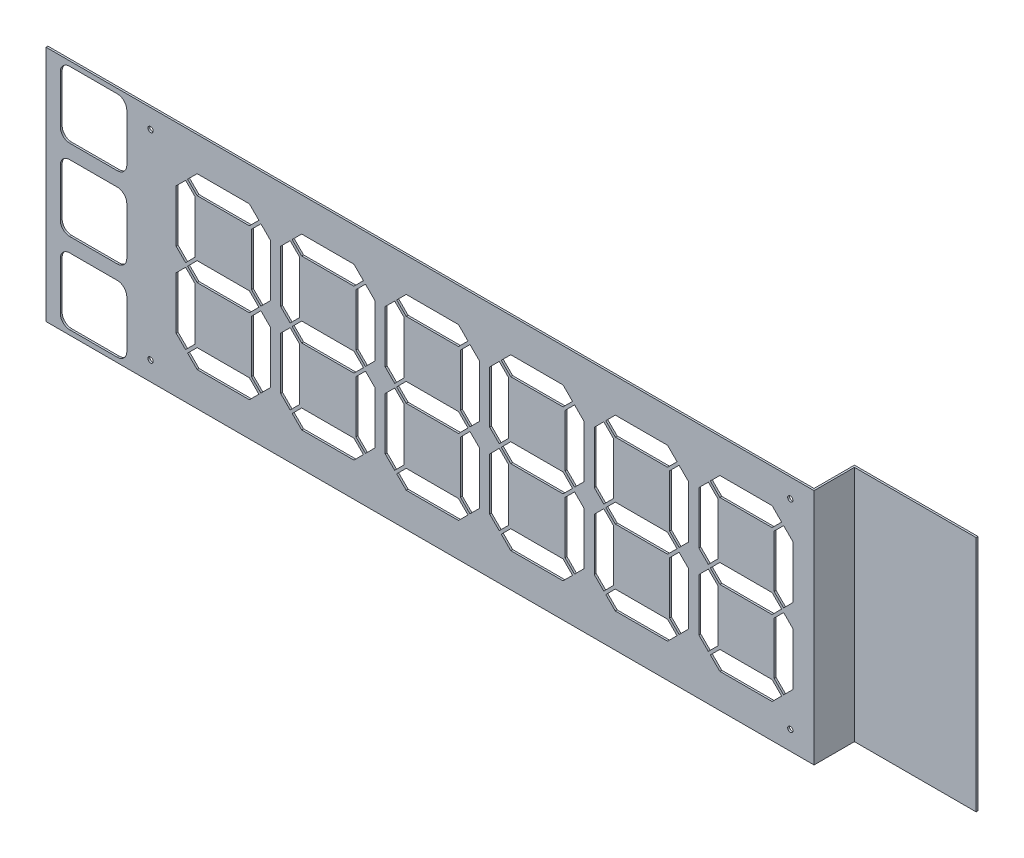
SolidWorks part; units mm, degrees
ref_plane "Plan de face" through (0, 0, 0) normal (0, 0, 1) x (1, 0, 0)
ref_plane "Plan de dessus" through (0, 0, 0) normal (0, 1, 0) x (1, 0, 0)
ref_plane "Plan de droite" through (0, 0, 0) normal (1, 0, 0) x (0, 0, -1)
sketch "Esquisse10" plane through (0, 0, 0) normal (0, 0, 1) x (1, 0, 0)
  line L264 (107.7211, -70.7055) -> (97.7211, -60.7055)
  line L265 (97.7211, -60.7055) -> (42.7211, -60.7055)
  line L266 (42.7211, -60.7055) -> (32.7211, -70.7055)
  line L267 (32.7211, -70.7055) -> (42.7211, -80.7055)
  line L268 (42.7211, -80.7055) -> (97.7211, -80.7055)
  line L269 (97.7211, -80.7055) -> (107.7211, -70.7055)
  line L270 (109.8425, -68.5842) -> (119.8425, -58.5842)
  line L271 (119.8425, -58.5842) -> (119.8425, -3.5842)
  line L272 (119.8425, -3.5842) -> (109.8425, 6.4158)
  line L273 (109.8425, 6.4158) -> (99.8425, -3.5842)
  line L274 (99.8425, -3.5842) -> (99.8425, -58.5842)
  line L275 (99.8425, -58.5842) -> (109.8425, -68.5842)
  line L276 (30.5998, -68.5842) -> (40.5998, -58.5842)
  line L277 (40.5998, -58.5842) -> (40.5998, -3.5842)
  line L278 (40.5998, -3.5842) -> (30.5998, 6.4158)
  line L279 (30.5998, 6.4158) -> (20.5998, -3.5842)
  line L280 (20.5998, -3.5842) -> (20.5998, -58.5842)
  line L281 (20.5998, -58.5842) -> (30.5998, -68.5842)
  line L282 (107.7211, 8.5372) -> (97.7211, 18.5372)
  line L283 (97.7211, 18.5372) -> (42.7211, 18.5372)
  line L284 (42.7211, 18.5372) -> (32.7211, 8.5372)
  line L285 (32.7211, 8.5372) -> (42.7211, -1.4628)
  line L286 (42.7211, -1.4628) -> (97.7211, -1.4628)
  line L287 (97.7211, -1.4628) -> (107.7211, 8.5372)
  line L288 (109.8425, 10.6585) -> (119.8425, 20.6585)
  line L289 (119.8425, 20.6585) -> (119.8425, 75.6585)
  line L290 (119.8425, 75.6585) -> (109.8425, 85.6585)
  line L291 (109.8425, 85.6585) -> (99.8425, 75.6585)
  line L292 (99.8425, 75.6585) -> (99.8425, 20.6585)
  line L293 (99.8425, 20.6585) -> (109.8425, 10.6585)
  line L294 (107.7211, 87.7798) -> (97.7211, 97.7798)
  line L295 (97.7211, 97.7798) -> (42.7211, 97.7798)
  line L296 (42.7211, 97.7798) -> (32.7211, 87.7798)
  line L297 (32.7211, 87.7798) -> (42.7211, 77.7798)
  line L298 (42.7211, 77.7798) -> (97.7211, 77.7798)
  line L299 (97.7211, 77.7798) -> (107.7211, 87.7798)
  line L300 (30.5998, 10.6585) -> (40.5998, 20.6585)
  line L301 (40.5998, 20.6585) -> (40.5998, 75.6585)
  line L302 (40.5998, 75.6585) -> (30.5998, 85.6585)
  line L303 (30.5998, 85.6585) -> (20.5998, 75.6585)
  line L304 (20.5998, 75.6585) -> (20.5998, 20.6585)
  line L305 (20.5998, 20.6585) -> (30.5998, 10.6585)
  line L306 (-0.1575, 10.6585) -> (9.8425, 20.6585)
  line L307 (9.8425, 20.6585) -> (9.8425, 75.6585)
  line L308 (9.8425, 75.6585) -> (-0.1575, 85.6585)
  line L309 (-0.1575, 85.6585) -> (-10.1575, 75.6585)
  line L310 (-10.1575, 75.6585) -> (-10.1575, 20.6585)
  line L311 (-10.1575, 20.6585) -> (-0.1575, 10.6585)
  line L312 (-0.1575, -68.5842) -> (9.8425, -58.5842)
  line L313 (9.8425, -58.5842) -> (9.8425, -3.5842)
  line L314 (9.8425, -3.5842) -> (-0.1575, 6.4158)
  line L315 (-0.1575, 6.4158) -> (-10.1575, -3.5842)
  line L316 (-10.1575, -3.5842) -> (-10.1575, -58.5842)
  line L317 (-10.1575, -58.5842) -> (-0.1575, -68.5842)
  line L318 (-2.2789, -70.7055) -> (-12.2789, -60.7055)
  line L319 (-12.2789, -60.7055) -> (-67.2789, -60.7055)
  line L320 (-67.2789, -60.7055) -> (-77.2789, -70.7055)
  line L321 (-77.2789, -70.7055) -> (-67.2789, -80.7055)
  line L322 (-67.2789, -80.7055) -> (-12.2789, -80.7055)
  line L323 (-12.2789, -80.7055) -> (-2.2789, -70.7055)
  line L324 (-79.4002, -68.5842) -> (-69.4002, -58.5842)
  line L325 (-69.4002, -58.5842) -> (-69.4002, -3.5842)
  line L326 (-69.4002, -3.5842) -> (-79.4002, 6.4158)
  line L327 (-79.4002, 6.4158) -> (-89.4002, -3.5842)
  line L328 (-89.4002, -3.5842) -> (-89.4002, -58.5842)
  line L329 (-89.4002, -58.5842) -> (-79.4002, -68.5842)
  line L330 (-2.2789, 8.5372) -> (-12.2789, 18.5372)
  line L331 (-12.2789, 18.5372) -> (-67.2789, 18.5372)
  line L332 (-67.2789, 18.5372) -> (-77.2789, 8.5372)
  line L333 (-77.2789, 8.5372) -> (-67.2789, -1.4628)
  line L334 (-67.2789, -1.4628) -> (-12.2789, -1.4628)
  line L335 (-12.2789, -1.4628) -> (-2.2789, 8.5372)
  line L336 (-79.4002, 10.6585) -> (-69.4002, 20.6585)
  line L337 (-69.4002, 20.6585) -> (-69.4002, 75.6585)
  line L338 (-69.4002, 75.6585) -> (-79.4002, 85.6585)
  line L339 (-79.4002, 85.6585) -> (-89.4002, 75.6585)
  line L340 (-89.4002, 75.6585) -> (-89.4002, 20.6585)
  line L341 (-89.4002, 20.6585) -> (-79.4002, 10.6585)
  line L342 (-2.2789, 87.7798) -> (-12.2789, 97.7798)
  line L343 (-12.2789, 97.7798) -> (-67.2789, 97.7798)
  line L344 (-67.2789, 97.7798) -> (-77.2789, 87.7798)
  line L345 (-77.2789, 87.7798) -> (-67.2789, 77.7798)
  line L346 (-67.2789, 77.7798) -> (-12.2789, 77.7798)
  line L347 (-12.2789, 77.7798) -> (-2.2789, 87.7798)
  line L348 (-110.1575, -68.5842) -> (-100.1575, -58.5842)
  line L349 (-100.1575, -58.5842) -> (-100.1575, -3.5842)
  line L350 (-100.1575, -3.5842) -> (-110.1575, 6.4158)
  line L351 (-110.1575, 6.4158) -> (-120.1575, -3.5842)
  line L352 (-120.1575, -3.5842) -> (-120.1575, -58.5842)
  line L353 (-120.1575, -58.5842) -> (-110.1575, -68.5842)
  line L354 (-112.2789, -70.7055) -> (-122.2789, -60.7055)
  line L355 (-122.2789, -60.7055) -> (-177.2789, -60.7055)
  line L356 (-177.2789, -60.7055) -> (-187.2789, -70.7055)
  line L357 (-187.2789, -70.7055) -> (-177.2789, -80.7055)
  line L358 (-177.2789, -80.7055) -> (-122.2789, -80.7055)
  line L359 (-122.2789, -80.7055) -> (-112.2789, -70.7055)
  line L360 (-189.4002, -68.5842) -> (-179.4002, -58.5842)
  line L361 (-179.4002, -58.5842) -> (-179.4002, -3.5842)
  line L362 (-179.4002, -3.5842) -> (-189.4002, 6.4158)
  line L363 (-189.4002, 6.4158) -> (-199.4002, -3.5842)
  line L364 (-199.4002, -3.5842) -> (-199.4002, -58.5842)
  line L365 (-199.4002, -58.5842) -> (-189.4002, -68.5842)
  line L366 (-112.2789, 8.5372) -> (-122.2789, 18.5372)
  line L367 (-122.2789, 18.5372) -> (-177.2789, 18.5372)
  line L368 (-177.2789, 18.5372) -> (-187.2789, 8.5372)
  line L369 (-187.2789, 8.5372) -> (-177.2789, -1.4628)
  line L370 (-177.2789, -1.4628) -> (-122.2789, -1.4628)
  line L371 (-122.2789, -1.4628) -> (-112.2789, 8.5372)
  line L372 (-110.1575, 10.6585) -> (-100.1575, 20.6585)
  line L373 (-100.1575, 20.6585) -> (-100.1575, 75.6585)
  line L374 (-100.1575, 75.6585) -> (-110.1575, 85.6585)
  line L375 (-110.1575, 85.6585) -> (-120.1575, 75.6585)
  line L376 (-120.1575, 75.6585) -> (-120.1575, 20.6585)
  line L377 (-120.1575, 20.6585) -> (-110.1575, 10.6585)
  line L378 (-112.2789, 87.7798) -> (-122.2789, 97.7798)
  line L379 (-122.2789, 97.7798) -> (-177.2789, 97.7798)
  line L380 (-177.2789, 97.7798) -> (-187.2789, 87.7798)
  line L381 (-187.2789, 87.7798) -> (-177.2789, 77.7798)
  line L382 (-177.2789, 77.7798) -> (-122.2789, 77.7798)
  line L383 (-122.2789, 77.7798) -> (-112.2789, 87.7798)
  line L384 (-189.4002, 10.6585) -> (-179.4002, 20.6585)
  line L385 (-179.4002, 20.6585) -> (-179.4002, 75.6585)
  line L386 (-179.4002, 75.6585) -> (-189.4002, 85.6585)
  line L387 (-189.4002, 85.6585) -> (-199.4002, 75.6585)
  line L388 (-199.4002, 75.6585) -> (-199.4002, 20.6585)
  line L389 (-199.4002, 20.6585) -> (-189.4002, 10.6585)
  line L390 (-222.2789, -70.7055) -> (-232.2789, -60.7055)
  line L391 (-232.2789, -60.7055) -> (-287.2789, -60.7055)
  line L392 (-287.2789, -60.7055) -> (-297.2789, -70.7055)
  line L393 (-297.2789, -70.7055) -> (-287.2789, -80.7055)
  line L394 (-287.2789, -80.7055) -> (-232.2789, -80.7055)
  line L395 (-232.2789, -80.7055) -> (-222.2789, -70.7055)
  line L396 (-220.1575, -68.5842) -> (-210.1575, -58.5842)
  line L397 (-210.1575, -58.5842) -> (-210.1575, -3.5842)
  line L398 (-210.1575, -3.5842) -> (-220.1575, 6.4158)
  line L399 (-220.1575, 6.4158) -> (-230.1575, -3.5842)
  line L400 (-230.1575, -3.5842) -> (-230.1575, -58.5842)
  line L401 (-230.1575, -58.5842) -> (-220.1575, -68.5842)
  line L402 (-299.4002, -68.5842) -> (-289.4002, -58.5842)
  line L403 (-289.4002, -58.5842) -> (-289.4002, -3.5842)
  line L404 (-289.4002, -3.5842) -> (-299.4002, 6.4158)
  line L405 (-299.4002, 6.4158) -> (-309.4002, -3.5842)
  line L406 (-309.4002, -3.5842) -> (-309.4002, -58.5842)
  line L407 (-309.4002, -58.5842) -> (-299.4002, -68.5842)
  line L408 (-222.2789, 8.5372) -> (-232.2789, 18.5372)
  line L409 (-232.2789, 18.5372) -> (-287.2789, 18.5372)
  line L410 (-287.2789, 18.5372) -> (-297.2789, 8.5372)
  line L411 (-297.2789, 8.5372) -> (-287.2789, -1.4628)
  line L412 (-287.2789, -1.4628) -> (-232.2789, -1.4628)
  line L413 (-232.2789, -1.4628) -> (-222.2789, 8.5372)
  line L414 (-220.1575, 10.6585) -> (-210.1575, 20.6585)
  line L415 (-210.1575, 20.6585) -> (-210.1575, 75.6585)
  line L416 (-210.1575, 75.6585) -> (-220.1575, 85.6585)
  line L417 (-220.1575, 85.6585) -> (-230.1575, 75.6585)
  line L418 (-230.1575, 75.6585) -> (-230.1575, 20.6585)
  line L419 (-230.1575, 20.6585) -> (-220.1575, 10.6585)
  line L420 (-299.4002, 10.6585) -> (-289.4002, 20.6585)
  line L421 (-289.4002, 20.6585) -> (-289.4002, 75.6585)
  line L422 (-289.4002, 75.6585) -> (-299.4002, 85.6585)
  line L423 (-299.4002, 85.6585) -> (-309.4002, 75.6585)
  line L424 (-309.4002, 75.6585) -> (-309.4002, 20.6585)
  line L425 (-309.4002, 20.6585) -> (-299.4002, 10.6585)
  line L426 (-222.2789, 87.7798) -> (-232.2789, 97.7798)
  line L427 (-232.2789, 97.7798) -> (-287.2789, 97.7798)
  line L428 (-287.2789, 97.7798) -> (-297.2789, 87.7798)
  line L429 (-297.2789, 87.7798) -> (-287.2789, 77.7798)
  line L430 (-287.2789, 77.7798) -> (-232.2789, 77.7798)
  line L431 (-232.2789, 77.7798) -> (-222.2789, 87.7798)
  line L432 (-332.2789, -70.7055) -> (-342.2789, -60.7055)
  line L433 (-342.2789, -60.7055) -> (-397.2789, -60.7055)
  line L434 (-397.2789, -60.7055) -> (-407.2789, -70.7055)
  line L435 (-407.2789, -70.7055) -> (-397.2789, -80.7055)
  line L436 (-397.2789, -80.7055) -> (-342.2789, -80.7055)
  line L437 (-342.2789, -80.7055) -> (-332.2789, -70.7055)
  line L438 (-330.1575, -68.5842) -> (-320.1575, -58.5842)
  line L439 (-320.1575, -58.5842) -> (-320.1575, -3.5842)
  line L440 (-320.1575, -3.5842) -> (-330.1575, 6.4158)
  line L441 (-330.1575, 6.4158) -> (-340.1575, -3.5842)
  line L442 (-340.1575, -3.5842) -> (-340.1575, -58.5842)
  line L443 (-340.1575, -58.5842) -> (-330.1575, -68.5842)
  line L444 (-409.4002, -68.5842) -> (-399.4002, -58.5842)
  line L445 (-399.4002, -58.5842) -> (-399.4002, -3.5842)
  line L446 (-399.4002, -3.5842) -> (-409.4002, 6.4158)
  line L447 (-409.4002, 6.4158) -> (-419.4002, -3.5842)
  line L448 (-419.4002, -3.5842) -> (-419.4002, -58.5842)
  line L449 (-419.4002, -58.5842) -> (-409.4002, -68.5842)
  line L450 (-332.2789, 8.5372) -> (-342.2789, 18.5372)
  line L451 (-342.2789, 18.5372) -> (-397.2789, 18.5372)
  line L452 (-397.2789, 18.5372) -> (-407.2789, 8.5372)
  line L453 (-407.2789, 8.5372) -> (-397.2789, -1.4628)
  line L454 (-397.2789, -1.4628) -> (-342.2789, -1.4628)
  line L455 (-342.2789, -1.4628) -> (-332.2789, 8.5372)
  line L456 (-330.1575, 10.6585) -> (-320.1575, 20.6585)
  line L457 (-320.1575, 20.6585) -> (-320.1575, 75.6585)
  line L458 (-320.1575, 75.6585) -> (-330.1575, 85.6585)
  line L459 (-330.1575, 85.6585) -> (-340.1575, 75.6585)
  line L460 (-340.1575, 75.6585) -> (-340.1575, 20.6585)
  line L461 (-340.1575, 20.6585) -> (-330.1575, 10.6585)
  line L462 (-332.2789, 87.7798) -> (-342.2789, 97.7798)
  line L463 (-342.2789, 97.7798) -> (-397.2789, 97.7798)
  line L464 (-397.2789, 97.7798) -> (-407.2789, 87.7798)
  line L465 (-407.2789, 87.7798) -> (-397.2789, 77.7798)
  line L466 (-397.2789, 77.7798) -> (-342.2789, 77.7798)
  line L467 (-342.2789, 77.7798) -> (-332.2789, 87.7798)
  line L468 (-409.4002, 10.6585) -> (-399.4002, 20.6585)
  line L469 (-399.4002, 20.6585) -> (-399.4002, 75.6585)
  line L470 (-399.4002, 75.6585) -> (-409.4002, 85.6585)
  line L471 (-409.4002, 85.6585) -> (-419.4002, 75.6585)
  line L472 (-419.4002, 75.6585) -> (-419.4002, 20.6585)
  line L473 (-419.4002, 20.6585) -> (-409.4002, 10.6585)
  line L474 (-440.1575, -68.5842) -> (-430.1575, -58.5842)
  line L475 (-430.1575, -58.5842) -> (-430.1575, -3.5842)
  line L476 (-430.1575, -3.5842) -> (-440.1575, 6.4158)
  line L477 (-440.1575, 6.4158) -> (-450.1575, -3.5842)
  line L478 (-450.1575, -3.5842) -> (-450.1575, -58.5842)
  line L479 (-450.1575, -58.5842) -> (-440.1575, -68.5842)
  line L480 (-442.2789, -70.7055) -> (-452.2789, -60.7055)
  line L481 (-452.2789, -60.7055) -> (-507.2789, -60.7055)
  line L482 (-507.2789, -60.7055) -> (-517.2789, -70.7055)
  line L483 (-517.2789, -70.7055) -> (-507.2789, -80.7055)
  line L484 (-507.2789, -80.7055) -> (-452.2789, -80.7055)
  line L485 (-452.2789, -80.7055) -> (-442.2789, -70.7055)
  line L486 (-519.4002, -68.5842) -> (-509.4002, -58.5842)
  line L487 (-509.4002, -58.5842) -> (-509.4002, -3.5842)
  line L488 (-509.4002, -3.5842) -> (-519.4002, 6.4158)
  line L489 (-519.4002, 6.4158) -> (-529.4002, -3.5842)
  line L490 (-529.4002, -3.5842) -> (-529.4002, -58.5842)
  line L491 (-529.4002, -58.5842) -> (-519.4002, -68.5842)
  line L492 (-442.2789, 8.5372) -> (-452.2789, 18.5372)
  line L493 (-452.2789, 18.5372) -> (-507.2789, 18.5372)
  line L494 (-507.2789, 18.5372) -> (-517.2789, 8.5372)
  line L495 (-517.2789, 8.5372) -> (-507.2789, -1.4628)
  line L496 (-507.2789, -1.4628) -> (-452.2789, -1.4628)
  line L497 (-452.2789, -1.4628) -> (-442.2789, 8.5372)
  line L498 (-440.1575, 10.6585) -> (-430.1575, 20.6585)
  line L499 (-430.1575, 20.6585) -> (-430.1575, 75.6585)
  line L500 (-430.1575, 75.6585) -> (-440.1575, 85.6585)
  line L501 (-440.1575, 85.6585) -> (-450.1575, 75.6585)
  line L502 (-450.1575, 75.6585) -> (-450.1575, 20.6585)
  line L503 (-450.1575, 20.6585) -> (-440.1575, 10.6585)
  line L504 (-519.4002, 10.6585) -> (-509.4002, 20.6585)
  line L505 (-509.4002, 20.6585) -> (-509.4002, 75.6585)
  line L506 (-509.4002, 75.6585) -> (-519.4002, 85.6585)
  line L507 (-519.4002, 85.6585) -> (-529.4002, 75.6585)
  line L508 (-529.4002, 75.6585) -> (-529.4002, 20.6585)
  line L509 (-529.4002, 20.6585) -> (-519.4002, 10.6585)
  line L510 (-442.2789, 87.7798) -> (-452.2789, 97.7798)
  line L511 (-452.2789, 97.7798) -> (-507.2789, 97.7798)
  line L512 (-507.2789, 97.7798) -> (-517.2789, 87.7798)
  line L513 (-517.2789, 87.7798) -> (-507.2789, 77.7798)
  line L514 (-507.2789, 77.7798) -> (-452.2789, 77.7798)
  line L515 (-452.2789, 77.7798) -> (-442.2789, 87.7798)
  line L516 (-591.2895, -111.4628) -> (-641.2895, -111.4628)
  line L517 (-651.2895, -101.4628) -> (-651.2895, -51.4628)
  line L518 (-581.2895, -51.4628) -> (-581.2895, -101.4628)
  line L519 (-641.2895, -41.4628) -> (-591.2895, -41.4628)
  line L520 (-651.2895, -16.4628) -> (-651.2895, 33.5372)
  line L521 (-591.2895, -26.4628) -> (-641.2895, -26.4628)
  line L522 (-581.2895, 33.5372) -> (-581.2895, -16.4628)
  line L523 (-641.2895, 43.5372) -> (-591.2895, 43.5372)
  line L524 (-641.2895, 128.5372) -> (-591.2895, 128.5372)
  line L525 (-651.2895, 68.5372) -> (-651.2895, 118.5372)
  line L526 (-591.2895, 58.5372) -> (-641.2895, 58.5372)
  line L527 (-581.2895, 118.5372) -> (-581.2895, 68.5372)
  line L532 (139.8425, -116.4628) -> (-666.2895, -116.4628)
  line L533 (-704.7789, -106.4628) -> (-704.7789, 123.5372) construction
  line L534 (295.2211, 123.5372) -> (295.2211, -106.4628) construction
  line L535 (-666.2895, 133.5372) -> (139.8425, 133.5372)
  line L540 (266.296, -78.4133) -> (166.296, -78.4133) construction
  line L541 (266.296, 121.5867) -> (266.296, -78.4133) construction
  line L542 (166.296, 121.5867) -> (266.296, 121.5867) construction
  line L543 (166.296, -78.4133) -> (166.296, 121.5867) construction
  line L544 (-666.2895, 133.5372) -> (-666.2895, -116.4628)
  line L545 (139.8425, 133.5372) -> (139.8425, -116.4628)
  line L546 (285.2211, 133.5372) -> (139.8425, 133.5372) construction
  line L547 (139.8425, -116.4628) -> (285.2211, -116.4628) construction
  line L548 (-666.2895, 133.5372) -> (-694.7789, 133.5372) construction
  line L549 (-666.2895, -116.4628) -> (-694.7789, -116.4628) construction
  arc A12 (-591.2895, -111.4628) -> (-581.2895, -101.4628) centre (-591.2895, -101.4628) ccw
  arc A13 (-651.2895, -101.4628) -> (-641.2895, -111.4628) centre (-641.2895, -101.4628) ccw
  arc A14 (-641.2895, -41.4628) -> (-651.2895, -51.4628) centre (-641.2895, -51.4628) ccw
  arc A15 (-581.2895, -51.4628) -> (-591.2895, -41.4628) centre (-591.2895, -51.4628) ccw
  arc A16 (-641.2895, 43.5372) -> (-651.2895, 33.5372) centre (-641.2895, 33.5372) ccw
  arc A17 (-651.2895, -16.4628) -> (-641.2895, -26.4628) centre (-641.2895, -16.4628) ccw
  arc A18 (-591.2895, -26.4628) -> (-581.2895, -16.4628) centre (-591.2895, -16.4628) ccw
  arc A19 (-581.2895, 33.5372) -> (-591.2895, 43.5372) centre (-591.2895, 33.5372) ccw
  arc A20 (-641.2895, 128.5372) -> (-651.2895, 118.5372) centre (-641.2895, 118.5372) ccw
  arc A21 (-651.2895, 68.5372) -> (-641.2895, 58.5372) centre (-641.2895, 68.5372) ccw
  arc A22 (-591.2895, 58.5372) -> (-581.2895, 68.5372) centre (-591.2895, 68.5372) ccw
  arc A23 (-581.2895, 118.5372) -> (-591.2895, 128.5372) centre (-591.2895, 118.5372) ccw
  arc A28 (285.2211, -116.4628) -> (295.2211, -106.4628) centre (285.2211, -106.4628) ccw construction
  arc A29 (-704.7789, -106.4628) -> (-694.7789, -116.4628) centre (-694.7789, -106.4628) ccw construction
  arc A30 (-694.7789, 133.5372) -> (-704.7789, 123.5372) centre (-694.7789, 123.5372) ccw construction
  arc A31 (295.2211, 123.5372) -> (285.2211, 133.5372) centre (285.2211, 123.5372) ccw construction
  point P308 (119.8425, 48.1585)
  dimension "D1" = 649.2426
  dimension "D2" = 771.132
  dimension "D3" = 15
  dimension "D4" = 20
extrude "Boss.-Extru.2" add sketch "Esquisse10" along normal blind 2
sketch "Esquisse11" plane through (0, -116.4628, 0) normal (0, -1, 0) x (1, 0, 0)
  line L1 (139.8425, 2) -> (141.8425, 2)
  line L2 (139.8425, 2) -> (139.8425, -35.5)
  line L4 (141.8425, 2) -> (141.8425, -40.5)
  line L6 (141.8425, -40.5) -> (269.8425, -40.5)
  line L7 (139.8425, -35.5) -> (139.8425, -42.5)
  line L8 (139.8425, -42.5) -> (269.8425, -42.5)
  line L9 (269.8425, -40.5) -> (269.8425, -42.5)
  dimension "D1" = 44.5
  dimension "D2" = 130
  dimension "D3" = 2
  dimension "D4" = 2
extrude "Boss.-Extru.3" add sketch "Esquisse11" against normal up to surface (250 mm away) up to face at (-263.2235, 133.5372, 1)
hole_wizard "Dégagement M52" positions "Esquisse3D2" profile "Esquisse13" hole size "M5" standard "Ansi Metric"
sketch3d "Esquisse3D2"
  line L0 (141.8425, 133.5372, 2) -> (-666.2895, 133.5372, 2) construction
  line L1 (-581.2895, 68.5372, 2) -> (-581.2895, 118.5372, 2) construction
  line L2 (-581.2895, -101.4628, 2) -> (-581.2895, -51.4628, 2) construction
  line L3 (-666.2895, -116.4628, 2) -> (141.8425, -116.4628, 2) construction
  line L4 (141.8425, 133.5372, 2) -> (141.8425, -116.4628, 2) construction
  point P0 (-556.2895, 113.5372, 2)
  point P2 (-556.2895, -96.4628, 2)
  point P4 (116.8425, 113.5372, 2)
  point P6 (116.8425, -96.4628, 2)
  dimension "D1" = 20
  dimension "D2" = 25
  dimension "D3" = 25
  dimension "D4" = 20
  dimension "D5" = 20
  dimension "D6" = 25
  dimension "D7" = 25
  dimension "D8" = 20
sketch "Esquisse13" plane through (-556.2895, 113.5372, 2) normal (1, 0, 0) x (0, -1, 0)
  line L0 (0, 0) -> (0, 16.6524)
  line L1 (0, 16.6524) -> (2.75, 15)
  line L2 (2.75, 15) -> (2.75, 0)
  line L5 (2.75, 0) -> (0, 0)
  line L10 (0, 16.6524) -> (-2.75, 15) construction
  line L11 (0, -6.35) -> (0, 107.95) construction
  dimension "Diamètre du perçage" = 5.5
  dimension "Profondeur du perçage" = 15
  dimension "Angle de pointe" = 118
